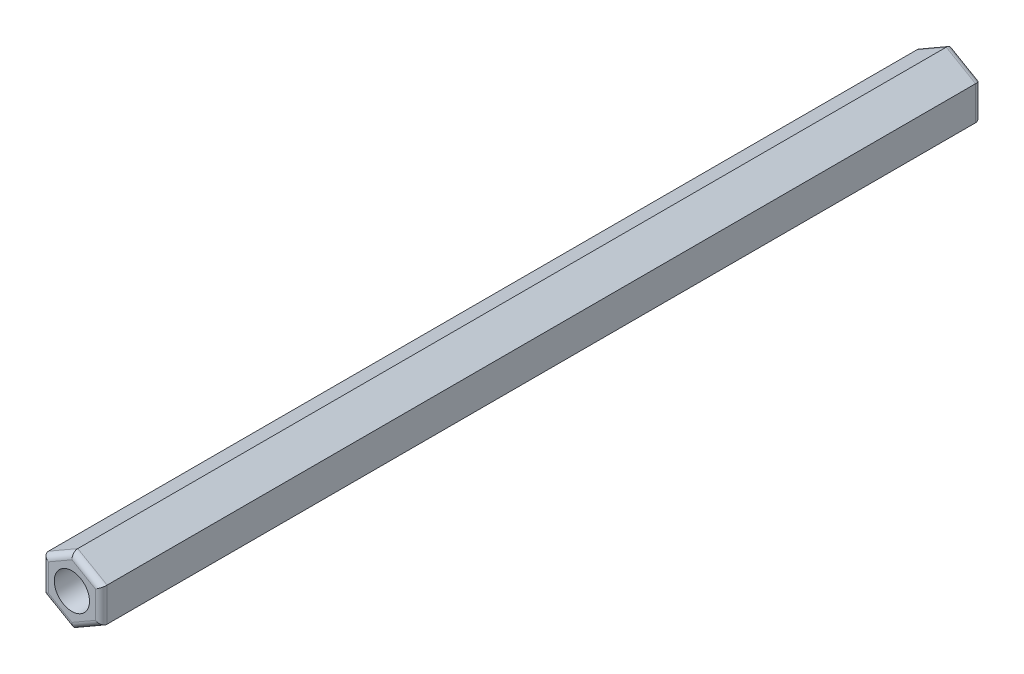
SolidWorks part; units mm, degrees
material "Liga de aço fundido"
ref_plane "Plano frontal" through (0, 0, 0) normal (0, 0, 1) x (1, 0, 0)
ref_plane "Plano superior" through (0, 0, 0) normal (0, 1, 0) x (1, 0, 0)
ref_plane "Plano direito" through (0, 0, 0) normal (1, 0, 0) x (0, 0, -1)
ref_plane "Plano1" through (0, 0, 0) normal (0, 0, -1) x (-1, 0, 0)
sketch "Esboço1" plane through (0, 0, 0) normal (0, 0, -1) x (-1, 0, 0)
  line L0 (67.5021, -1.4434) -> (70.0021, -2.8868)
  line L1 (70.0021, -2.8868) -> (72.5021, -1.4434)
  line L2 (72.5021, -1.4434) -> (72.5021, 1.4434)
  line L3 (72.5021, 1.4434) -> (70.0021, 2.8868)
  line L4 (70.0021, 2.8868) -> (67.5021, 1.4434)
  line L5 (67.5021, 1.4434) -> (67.5021, -1.4434)
extrude "Ressalto-extrusão1" add sketch "Esboço1" against normal blind 75
fillet "Filete1" radius 0.5 12 edges at (-71.2521, 2.1651, 0) (-72.5021, 0, 0) (-68.7521, 2.1651, 0) (-71.2521, -2.1651, 0) (-67.5021, 0, 0) (-68.7521, -2.1651, 0) (-71.2521, 2.1651, 75) (-72.5021, 0, 75) (-68.7521, 2.1651, 75) (-71.2521, -2.1651, 75) (-67.5021, 0, 75) (-68.7521, -2.1651, 75)
sketch "Esboço2" plane through (0, 0, 75) normal (0, 0, 1) x (1, 0, 0)
  circle A0 centre (-70.0021, 0) radius 1.5
  dimension "D1" = 3
extrude "Corte-extrusão1" cut sketch "Esboço2" against normal through all
